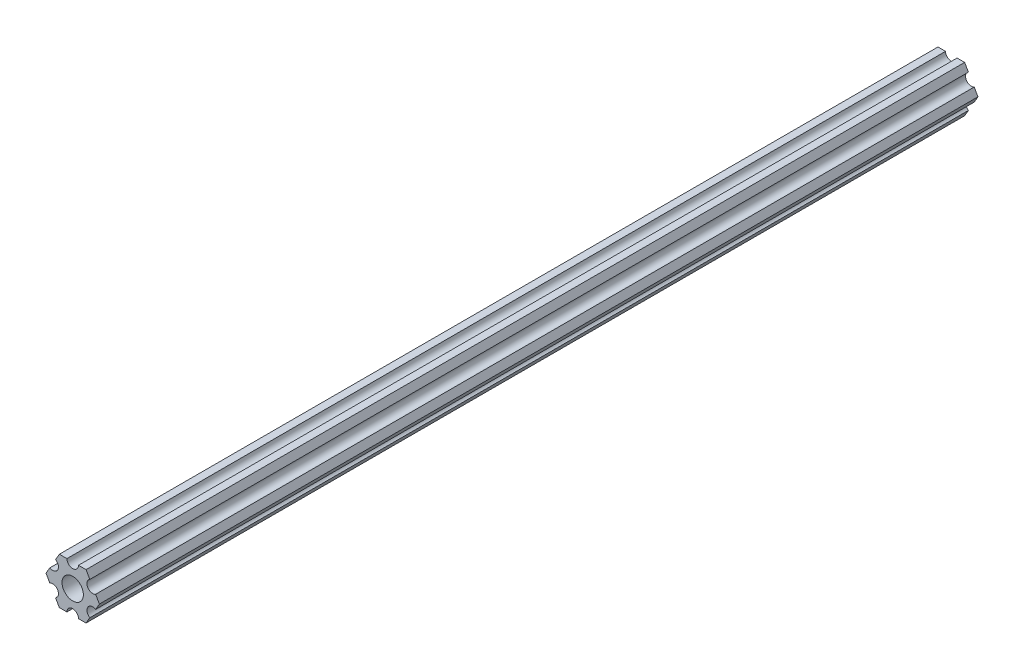
SolidWorks part; units mm, degrees
material "6061-T6 (SS)"
ref_plane "Front Plane" through (0, 0, 0) normal (0, 0, 1) x (1, 0, 0)
ref_plane "Top Plane" through (0, 0, 0) normal (0, 1, 0) x (1, 0, 0)
ref_plane "Right Plane" through (0, 0, 0) normal (1, 0, 0) x (0, 0, -1)
sketch "Sketch1" plane through (0, 0, 0) normal (0, 0, 1) x (1, 0, 0)
  line L0 (-4.7055, -4.5498) -> (-3.6662, -6.35)
  line L1 (-3.6662, -6.35) -> (-1.5875, -6.35)
  line L2 (1.5875, -6.35) -> (3.6662, -6.35)
  line L3 (3.6662, -6.35) -> (4.7055, -4.5498)
  line L4 (6.293, -1.8002) -> (7.3323, 0)
  line L5 (7.3323, 0) -> (6.293, 1.8002)
  line L6 (4.7055, 4.5498) -> (3.6662, 6.35)
  line L7 (3.6662, 6.35) -> (1.5875, 6.35)
  line L8 (-1.5875, 6.35) -> (-3.6662, 6.35)
  line L9 (-3.6662, 6.35) -> (-4.7055, 4.5498)
  line L10 (-6.293, 1.8002) -> (-7.3323, 0)
  line L11 (-7.3323, 0) -> (-6.293, -1.8002)
  circle A0 centre (0, 0) radius 2.9337
  arc A1 (-6.293, -1.8002) -> (-4.7055, -4.5498) centre (-5.4993, -3.175) cw
  arc A2 (-1.5875, -6.35) -> (1.5875, -6.35) centre (0, -6.35) cw
  arc A3 (4.7055, -4.5498) -> (6.293, -1.8002) centre (5.4993, -3.175) cw
  arc A4 (6.293, 1.8002) -> (4.7055, 4.5498) centre (5.4993, 3.175) cw
  arc A5 (1.5875, 6.35) -> (-1.5875, 6.35) centre (0, 6.35) cw
  arc A6 (-4.7055, 4.5498) -> (-6.293, 1.8002) centre (-5.4993, 3.175) cw
extrude "Boss-Extrude1" add sketch "Sketch1" against normal blind 241.3
